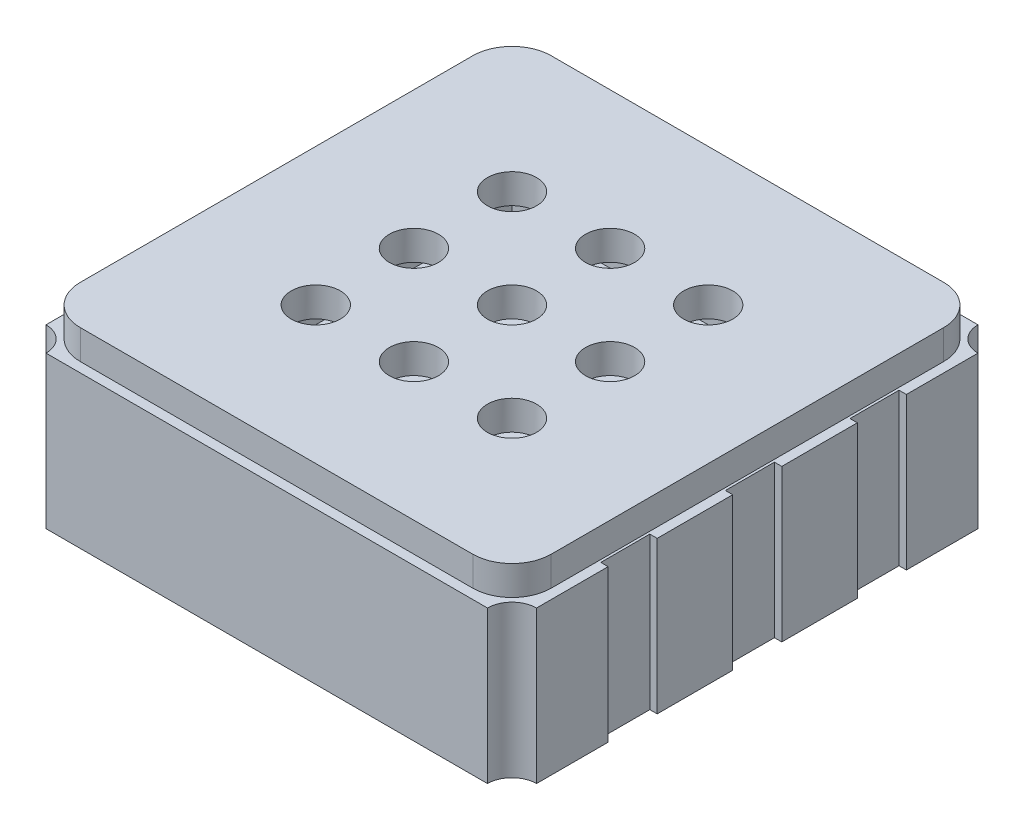
SolidWorks part; units mm, degrees
ref_plane "Front Plane" through (0, 0, 0) normal (0, 0, 1) x (1, 0, 0)
ref_plane "Top Plane" through (0, 0, 0) normal (0, 1, 0) x (1, 0, 0)
ref_plane "Right Plane" through (0, 0, 0) normal (1, 0, 0) x (0, 0, -1)
sketch "Sketch1" plane through (0, 0, 0) normal (0, 1, 0) x (1, 0, 0)
  line L0 (2.5, 5) -> (2.5, 0) construction
  line L1 (0, 0) -> (5, 0)
  line L2 (0, 0) -> (0, 5)
  line L3 (0, 5) -> (5, 5)
  line L4 (5, 0) -> (5, 5)
  line L5 (2.5, 0) -> (5, 2.5) construction
  line L6 (5, 2.5) -> (0, 2.5) construction
  arc A0 (0.25, 5) -> (0, 4.75) centre (0, 5) cw
  arc A1 (4.75, 5) -> (5, 4.75) centre (5, 5) ccw
  arc A2 (0.25, 0) -> (0, 0.25) centre (0, 0) ccw
  arc A3 (4.75, 0) -> (5, 0.25) centre (5, 0) cw
  dimension "D3" = 0.25
  dimension "D1" = 5
  dimension "D2" = 5
extrude "Boss-Extrude1" add sketch "Sketch1" along normal blind 1.55 contours L1 A3 L4 A1 L3 A0 L2 A2
sketch "Sketch2" plane through (0, 1.55, 0) normal (0, 1, 0) x (1, 0, 0)
  line L0 (2.5, 5) -> (2.5, 0) construction
  line L3 (5, 2.5) -> (0, 2.5) construction
  line L6 (0, 0.25) -> (0, 4.75) construction
  line L7 (0.5, 0.1) -> (4.5, 0.1)
  line L8 (0.1, 0.5) -> (0.1, 4.5)
  line L9 (0.5, 4.9) -> (4.5, 4.9)
  line L10 (4.9, 0.5) -> (4.9, 4.5)
  line L11 (0.1, 0.1) -> (4.9, 4.9) construction
  line L12 (0.1, 4.9) -> (4.9, 0.1) construction
  line L13 (5, 0.25) -> (5, 4.75) construction
  line L14 (0.25, 0) -> (4.75, 0) construction
  line L15 (0.25, 5) -> (4.75, 5) construction
  arc A0 (0.1, 0.5) -> (0.5, 0.1) centre (0.5, 0.5) ccw
  arc A1 (4.9, 0.5) -> (4.5, 0.1) centre (4.5, 0.5) cw
  arc A2 (4.5, 4.9) -> (4.9, 4.5) centre (4.5, 4.5) cw
  arc A3 (0.5, 4.9) -> (0.1, 4.5) centre (0.5, 4.5) ccw
  point P2 (0, 0)
  point P3 (0, 0)
  point P8 (0, 0)
  point P12 (2.5, 2.5)
  point P17 (0, 0)
  point P18 (0, 0)
  point P31 (0, 0)
  point P34 (0, 0)
  point P35 (0, 0)
  point P38 (0, 0)
  point P41 (0, 0)
  point P44 (0, 0)
  dimension "D3" = 0.4
  dimension "D1" = 4.8
  dimension "D2" = 4.8
extrude "Boss-Extrude2" add sketch "Sketch2" along normal blind 0.3
sketch "Sketch4" plane through (0, 0, 0) normal (0, -1, 0) x (1, 0, 0)
  line L0 (2.5, 0) -> (2.5, -5) construction
  line L1 (0.25, 0) -> (4.75, 0) construction
  line L2 (0.25, -5) -> (4.75, -5) construction
  line L3 (2.5, -5) -> (5, -2.5) construction
  line L4 (5, -0.25) -> (5, -4.75) construction
  line L5 (5, -2.5) -> (0, -2.5) construction
  line L6 (0, -0.25) -> (0, -4.75) construction
  line L7 (2.5, -1.23) -> (0, -1.23) construction
  line L8 (-0.075, -2.75) -> (0.075, -2.75)
  line L9 (-0.075, -2.75) -> (-0.075, -2.25)
  line L10 (-0.075, -2.25) -> (0.075, -2.25)
  line L11 (0.075, -2.75) -> (0.075, -2.25)
  line L12 (-0.075, -2.75) -> (0.075, -2.25) construction
  line L13 (-0.075, -2.25) -> (0.075, -2.75) construction
  line L14 (2.5, -3.77) -> (0, -3.77) construction
  line L15 (5.075, -0.98) -> (4.925, -0.98)
  line L16 (-0.075, -1.48) -> (0.075, -1.48)
  line L17 (-0.075, -1.48) -> (-0.075, -0.98)
  line L18 (-0.075, -0.98) -> (0.075, -0.98)
  line L19 (0.075, -1.48) -> (0.075, -0.98)
  line L20 (-0.075, -1.48) -> (0.075, -0.98) construction
  line L21 (-0.075, -0.98) -> (0.075, -1.48) construction
  line L22 (-0.075, -4.02) -> (0.075, -4.02)
  line L23 (-0.075, -4.02) -> (-0.075, -3.52)
  line L24 (-0.075, -3.52) -> (0.075, -3.52)
  line L25 (0.075, -4.02) -> (0.075, -3.52)
  line L26 (-0.075, -4.02) -> (0.075, -3.52) construction
  line L27 (-0.075, -3.52) -> (0.075, -4.02) construction
  line L28 (4.925, -1.48) -> (4.925, -0.98)
  line L29 (5.075, -1.48) -> (4.925, -1.48)
  line L30 (5.075, -1.48) -> (5.075, -0.98)
  line L31 (5.075, -2.25) -> (4.925, -2.25)
  line L32 (4.925, -2.75) -> (4.925, -2.25)
  line L33 (5.075, -2.75) -> (4.925, -2.75)
  line L34 (5.075, -2.75) -> (5.075, -2.25)
  line L35 (5.075, -3.52) -> (4.925, -3.52)
  line L36 (4.925, -4.02) -> (4.925, -3.52)
  line L37 (5.075, -4.02) -> (4.925, -4.02)
  line L38 (5.075, -4.02) -> (5.075, -3.52)
  dimension "D1" = 0.5
  dimension "D2" = 0.15
  dimension "D3" = 1.27
  dimension "D4" = 1.27
extrude "Cut-Extrude1" cut sketch "Sketch4" against normal up to surface (1.55 mm away) up to face at (2.5, 1.55, -2.5)
sketch "Sketch5" plane through (0, 1.55, 0) normal (0, 1, 0) x (1, 0, 0)
  line L0 (4.5, 4.9) -> (0.5, 4.9) construction
  line L1 (0.375, 0.375) -> (4.625, 0.375)
  line L2 (0.375, 0.375) -> (0.375, 4.625)
  line L3 (0.375, 4.625) -> (4.625, 4.625)
  line L4 (4.625, 0.375) -> (4.625, 4.625)
  line L5 (0.375, 0.375) -> (4.625, 4.625) construction
  line L6 (0.375, 4.625) -> (4.625, 0.375) construction
  line L7 (4.9, 0.5) -> (4.9, 4.5) construction
  point P0 (2.5, 2.5)
  point P7 (2.5, 4.9)
  point P10 (4.9, 2.5)
  dimension "D1" = 4.25
  dimension "D2" = 4.25
extrude "Cut-Extrude2" cut sketch "Sketch5" against normal blind 1
sketch "Sketch6" plane through (0, 1.85, 0) normal (0, 1, 0) x (1, 0, 0)
  line L0 (2.5, 4.9) -> (2.5, 0.1) construction
  line L1 (4.5, 4.9) -> (0.5, 4.9) construction
  line L2 (0.5, 0.1) -> (4.5, 0.1) construction
  line L3 (4.9, 2.5) -> (0.1, 2.5) construction
  line L4 (4.9, 0.5) -> (4.9, 4.5) construction
  line L5 (0.1, 4.5) -> (0.1, 0.5) construction
  circle A0 centre (2.5, 2.5) radius 0.25
  circle A1 centre (2.5, 1.5) radius 0.25
  circle A2 centre (2.5, 3.5) radius 0.25
  circle A3 centre (3.5, 1.5) radius 0.25
  circle A4 centre (3.5, 2.5) radius 0.25
  circle A5 centre (3.5, 3.5) radius 0.25
  circle A6 centre (1.5, 2.5) radius 0.25
  circle A7 centre (1.5, 3.5) radius 0.25
  circle A8 centre (1.5, 1.5) radius 0.25
  point P17 (0, 0)
  point P31 (0, 0)
  point P32 (0, 0)
  point P33 (0, 0)
  dimension "D1" = 0.5
  dimension "D6" = 1
  dimension "D7" = 1
  dimension "D8" = 1
  dimension "D9" = 1
  dimension "D2" = 2
  dimension "D3" = 2
  dimension "D4" = 2
  dimension "D5" = 2
extrude "Cut-Extrude3" cut sketch "Sketch6" against normal up to next
